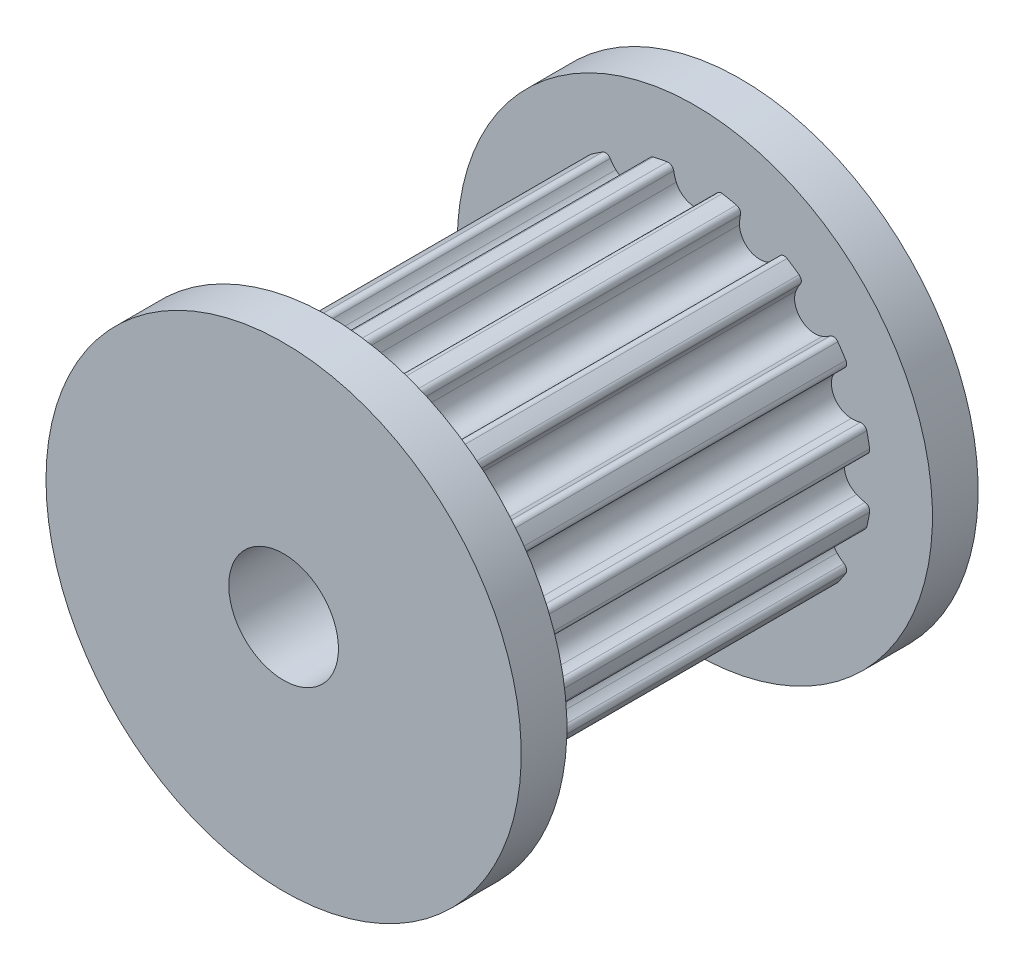
SolidWorks part; units mm, degrees
ref_plane "Front Plane" through (0, 0, 0) normal (1, 0, 0) x (0, 1, 0)
ref_plane "Top Plane" through (0, 0, 0) normal (0, 0, 1) x (0, 1, 0)
ref_plane "Right Plane" through (0, 0, 0) normal (0, 1, 0) x (-1, 0, 0)
other "Configuration Table"
sketch "Sketch1" plane through (0, 0, 0) normal (0, 1, 0) x (-1, 0, 0)
  line L0 (0, 0) -> (0, 12.5) construction
  line L1 (1.5, 12.5) -> (1.5, 0)
  line L2 (1.5, 0) -> (6.5, 0)
  line L3 (6.5, 0) -> (6.5, 1.25)
  line L4 (6.5, 1.25) -> (4.839, 1.25)
  line L5 (4.839, 1.25) -> (4.839, 11.25)
  line L6 (4.839, 11.25) -> (6.5, 11.25)
  line L7 (6.5, 11.25) -> (6.5, 12.5)
  line L8 (6.5, 12.5) -> (1.5, 12.5)
  dimension "boreDiameter" = 3
  dimension "flangeThickness" = 1.25
  dimension "beltWidth" = 10
  dimension "outerDiameter" = 13
  dimension "toothedDiameter" = 9.6779
revolve "Revolve1" add sketch "Sketch1" angle 360 about L0
sketch "Sketch2" plane through (0, 0, 1.25) normal (0, 0, 1) x (1, 0, 0)
  line L0 (0, 0) -> (0, 4.839) construction
  circle A0 centre (0, 0) radius 4.839 construction
  circle A1 centre (0, 0) radius 4.839 construction
  arc A2 (-0.7496, 4.7805) -> (-0.5784, 4.6571) centre (-0.7264, 4.6324) cw
  arc A3 (-0.5784, 4.6571) -> (-0.5088, 4.4222) centre (0.4079, 4.8217) ccw
  arc A4 (-0.5088, 4.4222) -> (0.5088, 4.4222) centre (0, 4.644) ccw
  arc A5 (0.7496, 4.7805) -> (0.5784, 4.6571) centre (0.7264, 4.6324) ccw
  arc A6 (0.5784, 4.6571) -> (0.5088, 4.4222) centre (-0.4079, 4.8217) cw
  arc A7 (-0.7496, 4.7805) -> (0.7496, 4.7805) centre (0, 0) cw
  point P10 (0, 4.089)
  dimension "R1" = 0.15
  dimension "R2" = 1
  dimension "R3" = 0.555
  dimension "h" = 0.75
extrude "Cut-Extrude1" cut sketch "Sketch2" along normal up to surface (10 mm away) contours A3 A4 A6 A5 A7 A2 up to face at (-6.5, 0, 11.25)
pattern_circular "CirPattern1" count 16 over 360 about axis through (0, 0, 0) along (0, 0, 1) of "Cut-Extrude1"
sketch "Sketch3" plane through (0, 0, 1.25) normal (0, 0, 1) x (1, 0, 0)
  circle A0 centre (0, 0) radius 5.469
  dimension "beltOutside" = 10.9379
